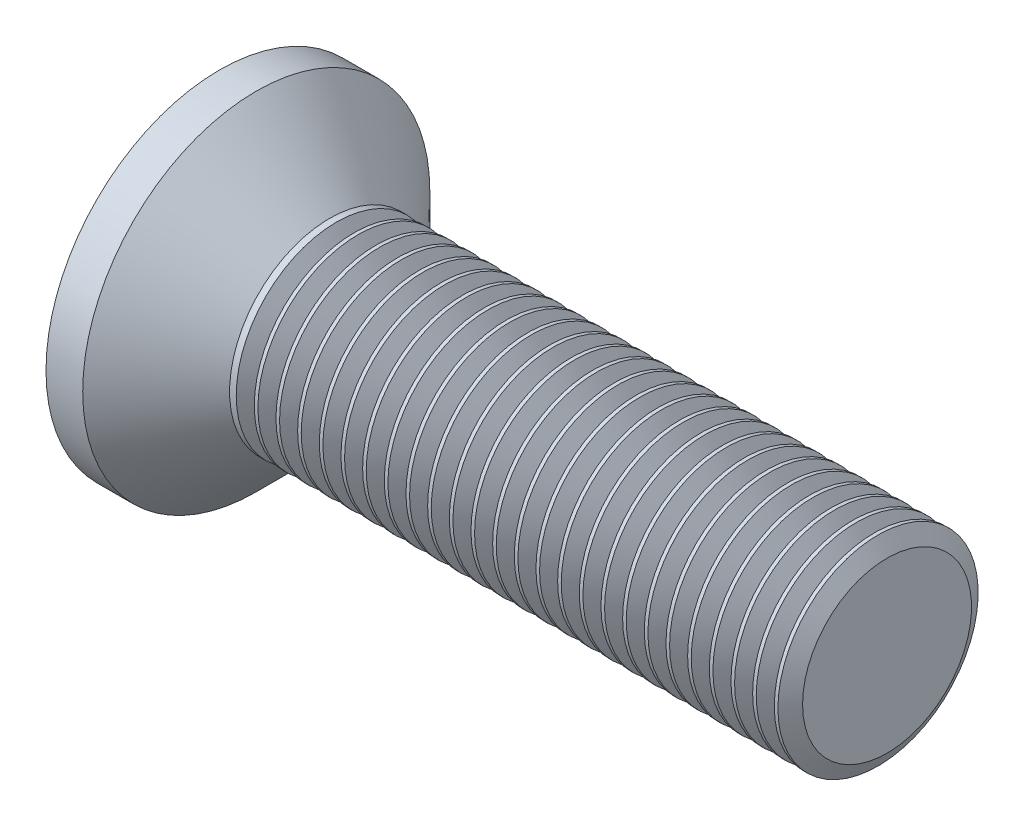
SolidWorks part; units mm, degrees
ref_plane "Front" through (0, 0, 0) normal (0, 0, 1) x (1, 0, 0)
ref_plane "Top" through (0, 0, 0) normal (0, 1, 0) x (1, 0, 0)
ref_plane "Right" through (0, 0, 0) normal (1, 0, 0) x (0, 0, -1)
other "Configuration Table"
sketch "Sketch1" plane through (0, 0, 0) normal (0, 0, 1) x (1, 0, 0)
  line L0 (10, 1.5) -> (2.65, 1.5)
  line L1 (2.65, 1.5) -> (1.65, 1.5)
  line L2 (1.65, 1.5) -> (0.55, 2.6)
  line L3 (0.55, 2.6) -> (0, 2.6)
  line L4 (10, 1.5) -> (10, 0)
  line L5 (4.5158, 0) -> (-89.8219, 0) construction
  line L6 (10, 0) -> (0, 0)
  line L7 (0, 2.6) -> (0, 0)
  dimension "d" = 3
  dimension "D1" = 45
  dimension "dk" = 5.2
  dimension "k" = 1.65
  dimension "l" = 10
  dimension "a" = 1
revolve "Base" add sketch "Sketch1" angle 360 about L5
cosmetic thread "ThreadCosmetic1" [suppressed] parameters "bb"=8.35, "THD_MINOR"=2.459
sketch "Sketch6" plane through (0, 0, 0) normal (1, 0, 0) x (0, 0, -1)
  line L0 (-1.9271, 0) -> (2.0512, 0) construction
  line L1 (0, 1.8651) -> (0, -2.0207) construction
  line L2 (0.32, 0.32) -> (0.32, 1.6)
  line L3 (0.32, 1.6) -> (-0.32, 1.6)
  line L4 (-0.32, 0.32) -> (-0.32, 1.6)
  line L5 (0.32, 0.32) -> (1.6, 0.32)
  line L6 (1.6, 0.32) -> (1.6, -0.32)
  line L7 (-1.6, 0.32) -> (-1.6, -0.32)
  line L8 (-0.32, 0.32) -> (-1.6, 0.32)
  line L9 (-0.32, -0.32) -> (-1.6, -0.32)
  line L10 (0.32, -0.32) -> (1.6, -0.32)
  line L11 (-0.32, -0.32) -> (-0.32, -1.6)
  line L12 (0.32, -1.6) -> (-0.32, -1.6)
  line L13 (0.32, -0.32) -> (0.32, -1.6)
  point P16 (-1.6, 0)
  point P17 (1.6, 0)
extrude "CrossRecess" cut sketch "Sketch6" along normal blind 0.825
draft "Draft9" type of draft neutral plane draft angle 30 faces to draft 4 face at (0.4125, 1.6, 0) face at (0.4125, 0, 1.6) face at (0.4125, -1.6, 0) face at (0.4125, 0, -1.6) neutral plane through (0, 2.6, 0) neutral plane normal (-1, 0, 0) parameters "D1"=30
fillet "Fillet5" radius 0.3 4 edges at (0.4125, -0.32, -0.32) (0.4125, 0.32, -0.32) (0.4125, 0.32, 0.32) (0.4125, -0.32, 0.32)
sketch "Sketch7" plane through (0, 0, 0) normal (1, 0, 0) x (0, 0, -1)
  line L0 (-2.0126, 0) -> (1.9757, 0) construction
  line L1 (0, 1.9314) -> (0, -2.0126) construction
  line L2 (0, 0) -> (1.5555, 1.5555) construction
  line L3 (0, 0.4782) -> (1.1314, 1.1314)
  line L4 (-1.5402, 1.5402) -> (0, 0) construction
  line L5 (0.4782, 0) -> (1.1314, 1.1314)
  line L6 (0, -0.4782) -> (1.1314, -1.1314)
  line L7 (0.4782, 0) -> (1.1314, -1.1314)
  line L8 (-0.4782, 0) -> (-1.1314, -1.1314)
  line L9 (0, -0.4782) -> (-1.1314, -1.1314)
  line L10 (-0.4782, 0) -> (-1.1314, 1.1314)
  line L11 (0, 0.4782) -> (-1.1314, 1.1314)
  dimension "D3" = 15
  dimension "m" = 3.2
extrude "Cut-Extrude3" [suppressed] cut sketch "Sketch7" along normal blind 10 draft 20
sketch "Sketch8" plane through (0, 0, 0) normal (0, 0, 1) x (1, 0, 0)
  line L0 (-15, 1.7705) -> (-16.25, 1.5)
  line L1 (-16.25, 1.5) -> (1.65, 1.5)
  line L3 (10, -1.5) -> (10, 1.5) construction
  line L6 (1.65, 1.5) -> (1.65, 6.5)
  line L7 (1.65, 6.5) -> (-15, 6.5)
  line L8 (-15, 6.5) -> (-15, 1.7705)
  line L9 (62.4753, 0.2705) -> (52.9594, 0.2705) construction
  dimension "D1" = 5
  dimension "x" = 1.25
  dimension "d" = 3
  dimension "THD_MINOR" = 2.459
  dimension "b" = 25
sketch "Sketch9" plane through (0, 0, 0) normal (0, 0, 1) x (1, 0, 0)
  line L0 (10, 1.2657) -> (10.1353, 1.5)
  line L1 (10.1353, 1.5) -> (10.1353, 1.7705)
  line L2 (10.1353, 1.7705) -> (9.8648, 1.7705)
  line L3 (9.8648, 1.7705) -> (9.8648, 1.5)
  line L4 (9.8648, 1.5) -> (10, 1.2657)
  line L5 (0, 0) -> (73.843, 0) construction
  line L6 (10, -1.5) -> (10, 1.5) construction
  dimension "D1" = 3
  dimension "D2" = 0.2705
revolve "Cut-Revolve10" cut sketch "Sketch9" angle 360 about L5
pattern_linear "LPattern10" count 26 spacing 0.3246 along (-1, 0, 0) of "Cut-Revolve10"
equation "\"D1@Sketch6\" = \"m@Sketch6\" / 5"
equation "\"D1@CrossRecess\" = \"k@Sketch1\" / 2"
equation "\"D1@Sketch9\" = \"d@Sketch1\""
equation "\"D2@Sketch9\" =  ( \"d@Sketch1\" - \"THD_MINOR@ThreadCosmetic1\" )  / 2"
equation "\"D3@LPattern10\" = \"D2@Sketch9\" * 1.2"
equation "\"D1@LPattern10\" = \"bb@ThreadCosmetic1\" / \"D3@LPattern10\" "
